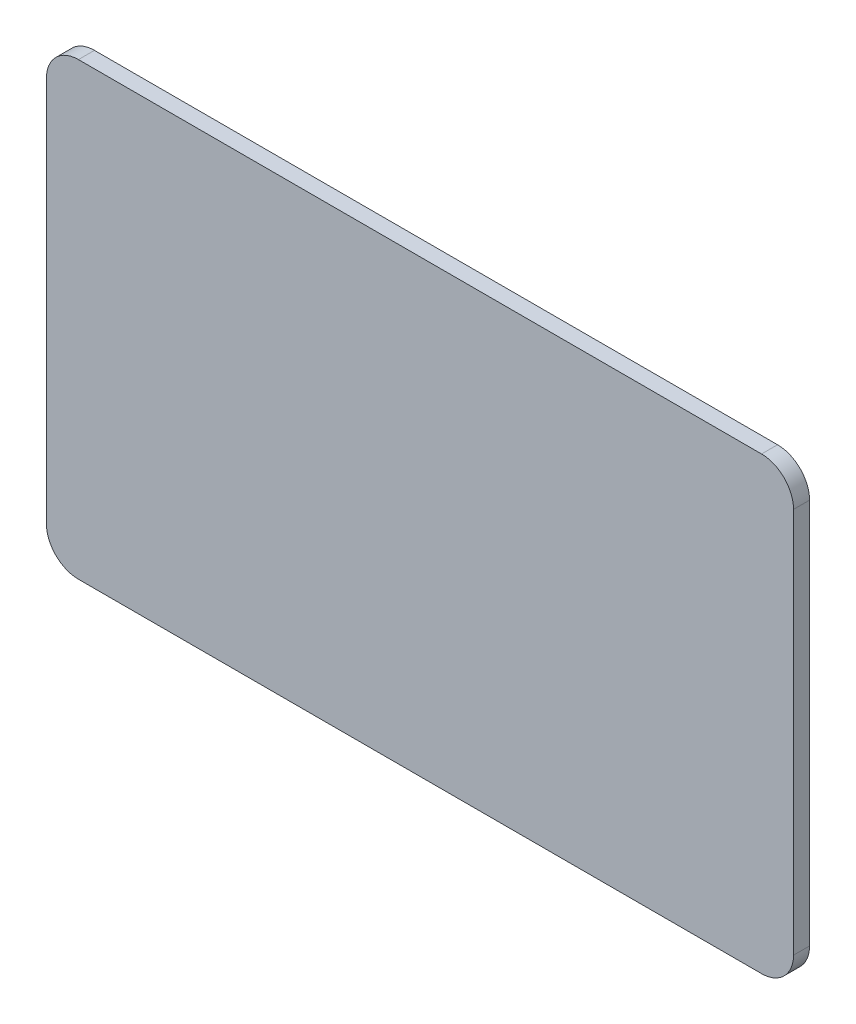
SolidWorks part; units mm, degrees
ref_plane "前基準面" through (0, 0, 0) normal (0, 0, 1) x (1, 0, 0)
ref_plane "上基準面" through (0, 0, 0) normal (0, 1, 0) x (1, 0, 0)
ref_plane "右基準面" through (0, 0, 0) normal (1, 0, 0) x (0, 0, -1)
sketch "草圖1" plane through (0, 0, 0) normal (0, 0, 1) x (1, 0, 0)
  line L0 (0, 13.7823) -> (0, -20.2177) construction
  line L2 (-23.3496, 10.8485) -> (23.3496, 10.8485)
  line L3 (-23.3496, 10.8485) -> (-23.3496, -17.2838)
  line L4 (-23.3496, -17.2838) -> (23.3496, -17.2838)
  line L5 (23.3496, 10.8485) -> (23.3496, -17.2838)
  line L6 (-23.3496, 10.8485) -> (23.3496, -17.2838) construction
  line L7 (-23.3496, -17.2838) -> (23.3496, 10.8485) construction
  point P3 (0, -3.2177)
extrude "填料-伸長1" add sketch "草圖1" along normal blind 1
fillet "圓角1" radius 2 4 edges at (23.3496, -17.2838, 0.5) (-23.3496, -17.2838, 0.5) (-23.3496, 10.8485, 0.5) (23.3496, 10.8485, 0.5)
